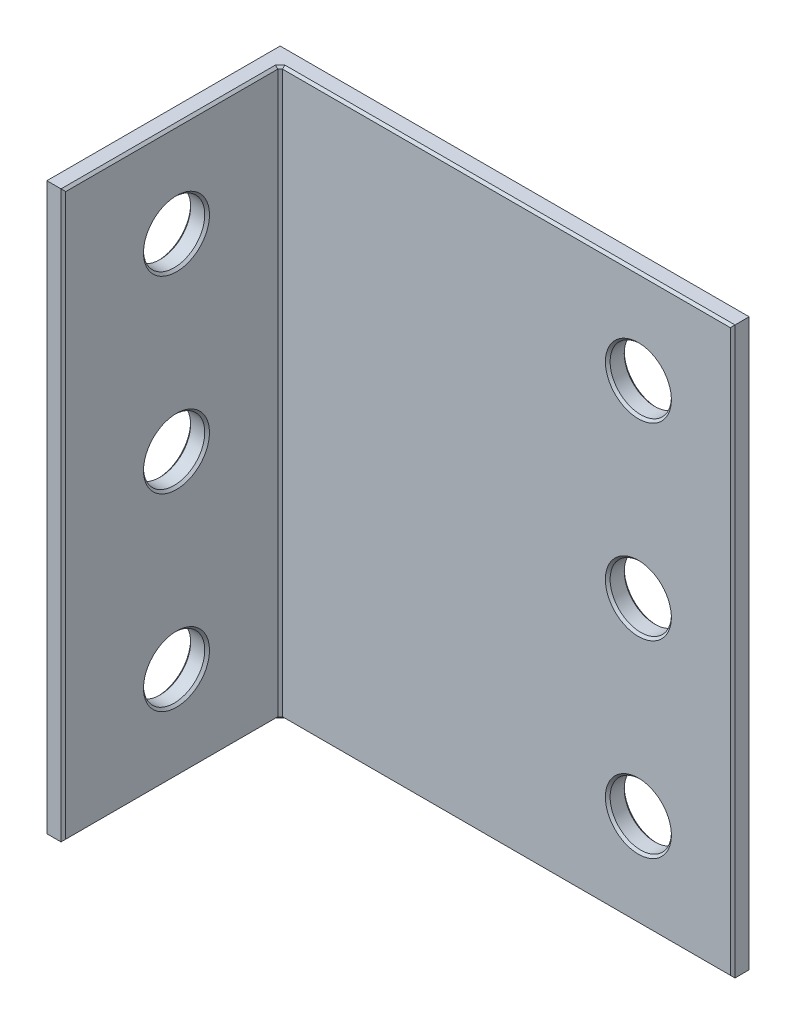
SolidWorks part; units mm, degrees
ref_plane "前视" through (0, 0, 0) normal (0, 0, 1) x (1, 0, 0)
ref_plane "上视" through (0, 0, 0) normal (0, 1, 0) x (1, 0, 0)
ref_plane "右视" through (0, 0, 0) normal (1, 0, 0) x (0, 0, -1)
sketch "草图1" plane through (0, 0, 0) normal (0, 0, 1) x (1, 0, 0)
  line L0 (160, 281.9635) -> (160, -120.4694) construction
  line L1 (0, 0) -> (200, 0)
  line L2 (0, 0) -> (0, 240)
  line L3 (0, 240) -> (200, 240)
  line L4 (200, 0) -> (200, 240)
  circle A0 centre (160, 40) radius 13
  circle A1 centre (160, 120) radius 13
  circle A2 centre (160, 200) radius 13
  dimension "D7" = 26
  dimension "D1" = 240
  dimension "D2" = 200
  dimension "D3" = 160
  dimension "D4" = 40
  dimension "D5" = 80
  dimension "D6" = 80
extrude "基体-拉伸" add sketch "草图1" along normal blind 8
sketch "草图2" plane through (0, 0, 8) normal (0, 0, 1) x (1, 0, 0)
  line L1 (0, 240) -> (8, 240)
  line L2 (0, 240) -> (0, 0)
  line L3 (0, 0) -> (8, 0)
  line L4 (8, 240) -> (8, 0)
  dimension "D1" = 8
extrude "凸台-拉伸1" add sketch "草图2" along normal blind 92
sketch "草图3" plane through (0, 0, 0) normal (-1, 0, 0) x (0, 0, 1)
  line L0 (52, 245.7913) -> (52, 32.4579) construction
  line L1 (0, 240) -> (0, 0) construction
  line L2 (100, 240) -> (0, 240) construction
  circle A0 centre (52, 200) radius 13
  circle A1 centre (52, 120) radius 13
  circle A2 centre (52, 40) radius 13
  dimension "D5" = 26
  dimension "D1" = 52
  dimension "D2" = 40
  dimension "D3" = 80
  dimension "D4" = 80
extrude "切除-拉伸1" cut sketch "草图3" against normal through all
chamfer "倒角1" distance 1 angle 45 26 edges at (173, 200, 0) (173, 40, 0) (173, 120, 0) (173, 120, 8) (173, 40, 8) (173, 200, 8) (100, 0, 0) (200, 120, 0) (100, 240, 0) (0, 240, 50) (0, 120, 100) (0, 0, 50) (0, 120, 0) (0, 200, 65) (0, 120, 65) (0, 40, 65) (200, 120, 8) (8, 120, 100) (8, 187, 52) (8, 107, 52) (8, 27, 52)
sketch "草图4" plane through (8, 0, 0) normal (1, 0, 0) x (0, 0, -1)
